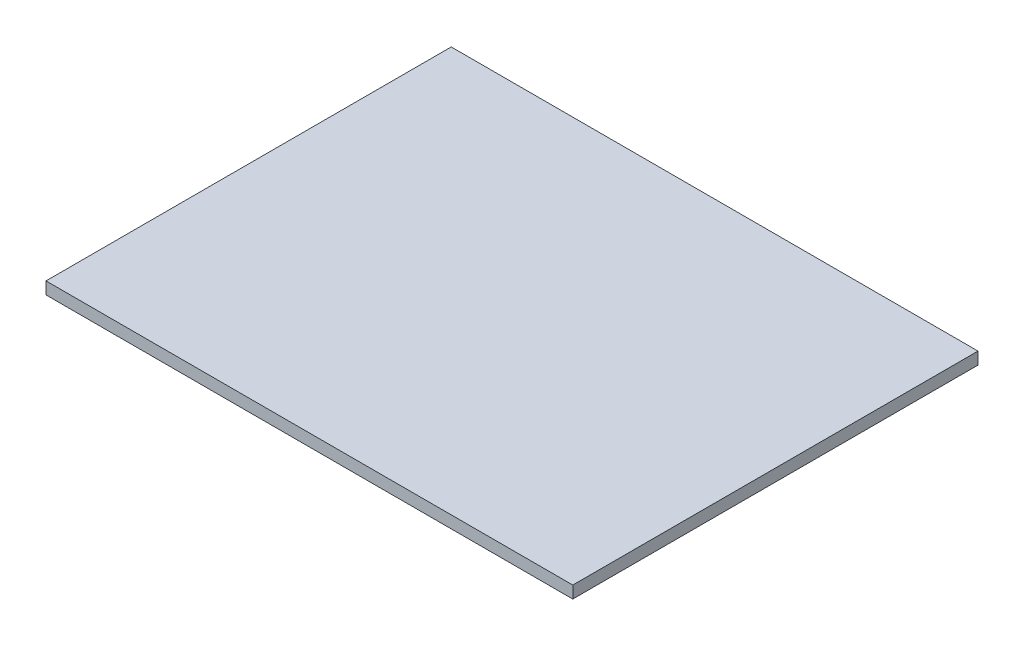
SolidWorks part; units mm, degrees
ref_plane "Front Plane" through (0, 0, 0) normal (0, 0, 1) x (1, 0, 0)
ref_plane "Top Plane" through (0, 0, 0) normal (0, 1, 0) x (1, 0, 0)
ref_plane "Right Plane" through (0, 0, 0) normal (1, 0, 0) x (0, 0, -1)
sketch "Sketch1" plane through (0, 0, 0) normal (0, 1, 0) x (1, 0, 0)
  line L1 (65, -50) -> (-65, -50)
  line L2 (65, -50) -> (65, 50)
  line L3 (65, 50) -> (-65, 50)
  line L4 (-65, -50) -> (-65, 50)
  line L5 (65, -50) -> (-65, 50) construction
  line L6 (65, 50) -> (-65, -50) construction
  point P0 (0, 0)
  dimension "D1" = 130
  dimension "D2" = 100
extrude "Boss-Extrude1" add sketch "Sketch1" along normal blind 3
equation "\"platform_L\"=130"
equation "\"D1@Sketch1\"=\"platform_L\""
equation "\"Platform_w\"=100"
equation "\"D2@Sketch1\"=\"Platform_w\""
